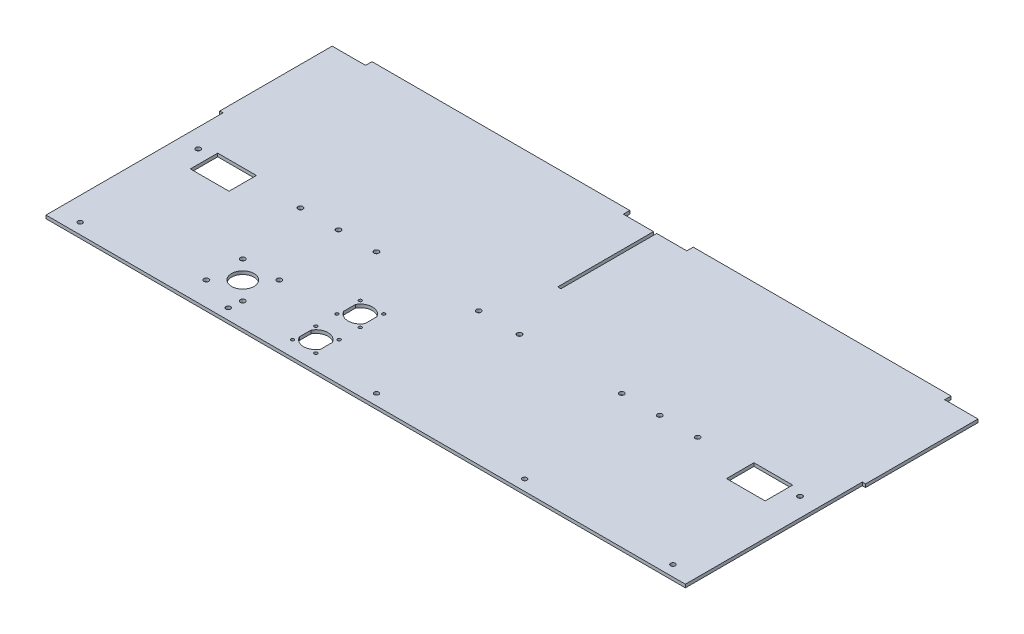
SolidWorks part; units mm, degrees
material "6061-T6 (SS)"
ref_plane "X-Y Datum" through (0, 0, 0) normal (0, 0, 1) x (1, 0, 0)
ref_plane "X-Z Datum" through (0, 0, 0) normal (0, 1, 0) x (1, 0, 0)
ref_plane "Y-Z Datum" through (0, 0, 0) normal (1, 0, 0) x (0, 0, -1)
sketch "Sketch1" plane through (0, 0, 0) normal (0, 1, 0) x (1, 0, 0)
  line L1 (0, 0) -> (629.9098, 0)
  line L2 (0, 0) -> (0, 147.6985)
  line L3 (0, 147.6985) -> (629.9098, 147.6985)
  line L4 (629.9098, 0) -> (629.9098, 147.6985)
extrude "Boss-Extrude1" add sketch "Sketch1" along normal blind 3.175
sketch "Sketch3" plane through (0, 0, -147.6985) normal (0, 0, -1) x (-1, 0, 0)
  line L0 (-629.9098, 0) -> (0, 0) construction
  line L1 (-629.9098, 0) -> (-629.9098, 3.175) construction
  line L2 (-629.9098, 3.175) -> (0, 3.175) construction
  line L3 (0, 0) -> (0, 3.175) construction
  line L4 (-600.2261, 0) -> (-346.2261, 0)
  line L5 (-600.2261, 0) -> (-600.2261, 3.175)
  line L6 (-600.2261, 3.175) -> (-346.2261, 3.175)
  line L7 (-346.2261, 0) -> (-346.2261, 3.175)
  line L8 (-283.6837, 0) -> (-29.6837, 0)
  line L9 (-283.6837, 0) -> (-283.6837, 3.175)
  line L10 (-283.6837, 3.175) -> (-29.6837, 3.175)
  line L11 (-29.6837, 0) -> (-29.6837, 3.175)
extrude "Boss-Extrude2" add sketch "Sketch3" along normal blind 6.35
sketch "Sketch4" plane through (0, 3.175, 0) normal (0, 1, 0) x (1, 0, 0)
  line L0 (346.2261, 147.6985) -> (283.6837, 147.6985) construction
  line L1 (313.3674, 53.332) -> (316.5424, 53.332)
  line L2 (313.3674, 53.332) -> (313.3674, 242.0649)
  line L3 (313.3674, 242.0649) -> (316.5424, 242.0649)
  line L4 (316.5424, 53.332) -> (316.5424, 242.0649)
  line L5 (313.3674, 53.332) -> (316.5424, 242.0649) construction
  line L6 (313.3674, 242.0649) -> (316.5424, 53.332) construction
  point P0 (314.9549, 147.6985)
extrude "Cut-Extrude1" cut sketch "Sketch4" against normal blind 3.175
sketch "Sketch6" plane through (0, 3.175, 0) normal (0, 1, 0) x (1, 0, 0)
  line L0 (314.9549, 53.332) -> (314.9549, 202.815) construction
  line L6 (629.9098, 36.9246) -> (633.0848, 36.9246)
  line L7 (633.0848, 147.6985) -> (633.0848, 36.9246)
  line L8 (629.9098, 147.6985) -> (633.0848, 147.6985)
  line L9 (629.9098, 147.6985) -> (629.9098, 36.9246)
  line L10 (0, 147.6985) -> (0, 36.9246)
  line L11 (0, 147.6985) -> (-3.175, 147.6985)
  line L12 (-3.175, 147.6985) -> (-3.175, 36.9246)
  line L13 (0, 36.9246) -> (-3.175, 36.9246)
extrude "Boss-Extrude4" add sketch "Sketch6" against normal blind 3.175
sketch "Sketch8" plane through (0, 3.175, 0) normal (0, 1, 0) x (1, 0, 0)
  line L1 (0, 0) -> (629.9098, 0)
  line L2 (0, 0) -> (0, -18.0442)
  line L3 (0, -18.0442) -> (629.9098, -18.0442)
  line L4 (629.9098, 0) -> (629.9098, -18.0442)
extrude "Boss-Extrude5" add sketch "Sketch8" against normal through all
sketch "Sketch9" plane through (0, 3.175, 0) normal (0, 1, 0) x (1, 0, 0)
  line L0 (0, -18.0442) -> (47.8104, -18.0442) construction
  line L1 (0, -18.0442) -> (629.9098, -18.0442) construction
  line L2 (314.9549, -18.0442) -> (314.9549, 180.2876) construction
  line L3 (30.0304, -36.0782) -> (65.5904, -36.0782)
  line L4 (30.0304, -36.0782) -> (30.0304, -0.0102)
  line L5 (30.0304, -0.0102) -> (65.5904, -0.0102)
  line L6 (65.5904, -36.0782) -> (65.5904, -0.0102)
  line L7 (30.0304, -36.0782) -> (65.5904, -0.0102) construction
  line L8 (30.0304, -0.0102) -> (65.5904, -36.0782) construction
  line L9 (599.8794, -0.0102) -> (564.3194, -0.0102)
  line L10 (564.3194, -36.0782) -> (564.3194, -0.0102)
  line L11 (599.8794, -36.0782) -> (564.3194, -36.0782)
  line L12 (599.8794, -36.0782) -> (599.8794, -0.0102)
extrude "Cut-Extrude2" [suppressed] cut sketch "Sketch9" against normal through all
sketch "Sketch10" plane through (0, 3.175, 0) normal (0, 1, 0) x (1, 0, 0)
  line L0 (313.3674, 53.332) -> (313.3674, -18.0442) construction
  line L1 (314.9549, -18.0442) -> (314.9549, -25.2417) construction
  line L2 (0, -18.0442) -> (629.9098, -18.0442) construction
  line L3 (313.3674, -18.0442) -> (281.6174, -18.0442) construction
  line L4 (348.2924, 0) -> (386.3924, 0) construction
  line L5 (281.6174, -18.0442) -> (243.5174, -18.0442) construction
  line L6 (281.6174, -18.0442) -> (281.6174, 0) construction
  line L7 (281.6174, 0) -> (243.5174, 0) construction
  line L8 (243.5174, -18.0442) -> (243.5174, 0) construction
  line L9 (386.3924, -18.0442) -> (386.3924, 0) construction
  line L10 (348.2924, -18.0442) -> (386.3924, -18.0442) construction
  line L11 (348.2924, -18.0442) -> (348.2924, 0) construction
  line L12 (0, -18.0442) -> (50.8, -18.0442) construction
  line L13 (0, -18.0442) -> (629.9098, -18.0442) construction
  line L22 (598.1598, 0) -> (560.0598, 0)
  line L23 (31.75, -36.0883) -> (69.85, -36.0883)
  line L24 (31.75, -36.0883) -> (31.75, 0)
  line L25 (31.75, 0) -> (69.85, 0)
  line L26 (69.85, -36.0883) -> (69.85, 0)
  line L27 (31.75, -36.0883) -> (69.85, 0) construction
  line L28 (31.75, 0) -> (69.85, -36.0883) construction
  line L29 (560.0598, -36.0883) -> (560.0598, 0)
  line L30 (598.1598, -36.0883) -> (560.0598, -36.0883)
  line L31 (598.1598, -36.0883) -> (598.1598, 0)
  line L32 (0, 36.9246) -> (0, -18.0442) construction
  dimension "D1" = 31.75
  dimension "D2" = 38.1
  dimension "D3" = 50.8
extrude "Cut-Extrude3" cut sketch "Sketch10" against normal through all
sketch "Sketch11" plane through (0, 3.175, 0) normal (0, 1, 0) x (1, 0, 0)
  line L2 (0, -18.0442) -> (0, -137.4242)
  line L3 (0, -137.4242) -> (629.9098, -137.4242)
  line L4 (629.9098, -18.0442) -> (629.9098, -137.4242)
  line L5 (314.9549, -18.0442) -> (629.9098, -137.4242) construction
  line L6 (0, -137.4242) -> (314.9549, -18.0442) construction
  line L7 (0, -18.0442) -> (31.75, -18.0442)
  line L8 (281.6174, -18.0442) -> (348.2924, -18.0442)
  line L10 (243.5174, -18.0442) -> (243.5174, -26.9519) construction
  line L11 (243.5174, -26.9519) -> (281.6174, -26.9519) construction
  line L12 (281.6174, -18.0442) -> (281.6174, -26.9519) construction
  line L14 (348.2924, -18.0442) -> (348.2924, -27.0662) construction
  line L15 (348.2924, -27.0662) -> (386.3924, -27.0662) construction
  line L16 (386.3924, -18.0442) -> (386.3924, -27.0662) construction
  line L17 (386.3924, -18.0442) -> (560.0598, -18.0442)
  line L18 (31.75, -18.0442) -> (31.75, -26.9519)
  line L19 (31.75, -26.9519) -> (69.85, -26.9519)
  line L20 (69.85, -26.9519) -> (69.85, -18.0442)
  line L21 (560.0598, -18.0442) -> (560.0598, -27.0662)
  line L22 (560.0598, -27.0662) -> (598.1598, -27.0662)
  line L23 (598.1598, -27.0662) -> (598.1598, -18.0442)
  line L24 (69.85, -18.0442) -> (243.5174, -18.0442)
  line L25 (598.1598, -18.0442) -> (629.9098, -18.0442)
  line L26 (243.5174, -18.0442) -> (281.6174, -18.0442)
  line L27 (348.2924, -18.0442) -> (386.3924, -18.0442)
  point P0 (314.9549, -18.0442)
extrude "Boss-Extrude6" add sketch "Sketch11" against normal through all
sketch "Sketch12" [suppressed] plane through (0, 3.175, 0) normal (0, 1, 0) x (1, 0, 0)
  line L1 (31.75, 0) -> (69.85, 0)
  line L2 (31.75, 0) -> (31.75, -18.0442)
  line L3 (31.75, -18.0442) -> (69.85, -18.0442)
  line L4 (69.85, 0) -> (69.85, -18.0442)
  line L5 (560.0598, 0) -> (598.1598, 0)
  line L6 (560.0598, 0) -> (560.0598, -18.0442)
  line L7 (560.0598, -18.0442) -> (598.1598, -18.0442)
  line L8 (598.1598, 0) -> (598.1598, -18.0442)
extrude "Boss-Extrude7" [suppressed] add sketch "Sketch12" against normal through all
sketch "Sketch13" plane through (0, 0, 0) normal (0, -1, 0) x (1, 0, 0)
  line L0 (229.2316, 116.5107) -> (229.2316, 105.1529) construction
  line L1 (249.2316, 116.5107) -> (249.2316, 105.1529) construction
  line L2 (249.2316, 72.6906) -> (249.2316, 61.3328) construction
  line L3 (229.2316, 72.6906) -> (229.2316, 61.3328) construction
  line L4 (249.7396, 116.6433) -> (249.7396, 105.0203)
  line L5 (228.7236, 116.6433) -> (228.7236, 105.0203)
  line L6 (249.7396, 72.8232) -> (249.7396, 61.2001)
  line L7 (228.7236, 72.8232) -> (228.7236, 61.2001)
  line L8 (2.2083, 136.32) -> (632.1181, 136.32) construction
  line L9 (2.2083, 136.32) -> (2.2083, 49.1456) construction
  line L10 (2.2083, 49.1456) -> (632.1181, 49.1456) construction
  line L11 (632.1181, 136.32) -> (632.1181, 49.1456) construction
  circle A0 centre (227.7316, 99.3318) radius 1.55
  circle A1 centre (227.7316, 122.3318) radius 1.55
  circle A2 centre (250.7316, 99.3318) radius 1.55
  circle A3 centre (250.7316, 122.3318) radius 1.55
  circle A4 centre (152.3285, 95.8779) radius 11.049
  circle A5 centre (227.7316, 78.5117) radius 1.55
  circle A6 centre (227.7316, 55.5117) radius 1.55
  circle A7 centre (250.7316, 55.5117) radius 1.55
  circle A8 centre (250.7316, 78.5117) radius 1.55
  arc A9 (249.2316, 72.6906) -> (229.2316, 72.6906) centre (239.2316, 67.0117) ccw construction
  arc A10 (249.2316, 61.3328) -> (229.2316, 61.3328) centre (239.2316, 67.0117) cw construction
  arc A11 (229.2316, 116.5107) -> (249.2316, 116.5107) centre (239.2316, 110.8318) cw construction
  arc A12 (229.2316, 105.1529) -> (249.2316, 105.1529) centre (239.2316, 110.8318) ccw construction
  arc A13 (228.7236, 105.0203) -> (249.7396, 105.0203) centre (239.2316, 110.8318) ccw
  arc A14 (228.7236, 116.6433) -> (249.7396, 116.6433) centre (239.2316, 110.8318) cw
  arc A15 (249.7396, 61.2001) -> (228.7236, 61.2001) centre (239.2316, 67.0117) cw
  arc A16 (249.7396, 72.8232) -> (228.7236, 72.8232) centre (239.2316, 67.0117) ccw
extrude "Cut-Extrude4" cut sketch "Sketch13" against normal through all
sketch "Sketch14" plane through (0, 0, 0) normal (0, -1, 0) x (1, 0, 0)
  line L0 (0, 137.4242) -> (653.3937, 137.4242) construction
  line L1 (0, 137.4242) -> (0, -17.9044) construction
  line L2 (0, -17.9044) -> (653.3937, -17.9044) construction
  line L3 (653.3937, 137.4242) -> (653.3937, -17.9044) construction
  point P0 (11.811, 127.2642)
  point P1 (163.383, 127.2642)
  point P2 (314.9549, 127.2642)
  point P3 (466.5269, 127.2642)
  point P4 (618.0988, 127.2642)
  point P5 (618.0988, 38.1102)
  point P6 (466.5269, 38.1102)
  point P7 (314.9549, 38.1102)
  point P8 (163.383, 38.1102)
  point P9 (11.811, 38.1102)
sketch "Sketch17" [suppressed] plane through (0, 3.175, 0) normal (0, 1, 0) x (1, 0, 0)
  line L1 (243.5174, -18.0442) -> (281.6174, -18.0442)
  line L2 (243.5174, -18.0442) -> (243.5174, 0)
  line L3 (243.5174, 0) -> (281.6174, 0)
  line L4 (281.6174, -18.0442) -> (281.6174, 0)
  line L5 (348.2924, -18.0442) -> (386.3924, -18.0442)
  line L6 (348.2924, -18.0442) -> (348.2924, 0)
  line L7 (348.2924, 0) -> (386.3924, 0)
  line L8 (386.3924, -18.0442) -> (386.3924, 0)
extrude "Cut-Extrude5" [suppressed] cut sketch "Sketch17" against normal through all
sketch "Sketch18" [suppressed] plane through (0, 3.175, 0) normal (0, 1, 0) x (1, 0, 0)
  line L0 (0, 36.9246) -> (0, -18.0442) construction
  line L1 (104.9274, 0.4059) -> (143.0274, 0.4059)
  line L2 (104.9274, 0.4059) -> (104.9274, -18.0442)
  line L3 (104.9274, -18.0442) -> (143.0274, -18.0442)
  line L4 (143.0274, 0.4059) -> (143.0274, -18.0442)
  line L10 (314.752, 53.332) -> (314.752, 40.2478) construction
  line L16 (386.3924, -18.0442) -> (629.9098, -18.0442) construction
  line L17 (567.7073, -18.0442) -> (529.6073, -18.0442)
  line L18 (567.7073, -18.0442) -> (567.7073, 0.4059)
  line L19 (567.7073, 0.4059) -> (529.6073, 0.4059)
  line L20 (529.6073, -18.0442) -> (529.6073, 0.4059)
  line L21 (0, -18.0442) -> (243.5174, -18.0442) construction
  line L22 (629.9098, -18.0442) -> (629.9098, 36.9246) construction
  dimension "D1" = 38.1
  dimension "D2" = 104.9274
  dimension "D3" = 38.1
  dimension "D4" = 62.2025
extrude "Cut-Extrude6" [suppressed] cut sketch "Sketch18" against normal through all
sketch "Sketch20" plane through (0, 0, 0) normal (0, -1, 0) x (1, 0, 0)
  line L0 (269.9465, 71.4811) -> (278.9364, 71.4811)
  line L1 (258.3414, 113.1615) -> (278.9364, 113.1615)
  line L2 (258.3414, 113.1615) -> (258.3414, 110.2194)
  line L3 (258.3414, 110.2194) -> (278.9364, 110.2194)
  line L4 (278.9364, 113.1615) -> (278.9364, 110.2194)
  line L5 (258.3414, 71.4811) -> (266.1871, 71.4811)
  line L6 (258.3414, 71.4811) -> (258.3414, 69.3563)
  line L7 (258.3414, 69.3563) -> (266.1871, 69.3563)
  line L8 (278.9364, 71.4811) -> (278.9364, 69.3563)
  line L9 (266.1871, 79) -> (269.9465, 79)
  line L10 (266.1871, 79) -> (266.1871, 71.4811)
  line L11 (266.1871, 61.8375) -> (269.9465, 61.8375)
  line L12 (269.9465, 79) -> (269.9465, 71.4811)
  line L13 (269.9465, 69.3563) -> (269.9465, 61.8375)
  line L14 (269.9465, 69.3563) -> (278.9364, 69.3563)
  line L15 (266.1871, 69.3563) -> (266.1871, 61.8375)
extrude "Cut-Extrude7" cut sketch "Sketch20" against normal blind 1.27
sketch "Sketch21" plane through (0, 3.175, 0) normal (0, 1, 0) x (1, 0, 0)
  line L0 (0, -137.4242) -> (8.6479, -137.4242) construction
  line L1 (0, -137.4242) -> (0, -125.2168) construction
  line L2 (0, -125.2168) -> (8.6479, -125.2168) construction
  line L3 (8.6479, -137.4242) -> (8.6479, -125.2168) construction
  line L4 (314.9549, 53.332) -> (314.9549, 36.3364) construction
  line L5 (313.3674, 53.332) -> (316.5424, 53.332) construction
  circle A1 centre (168.9435, -126.7866) radius 2.25
  circle A2 centre (314.9549, -126.7866) radius 2.25
  circle A3 centre (460.9663, -126.7866) radius 2.25
  circle A4 centre (606.9777, -126.7866) radius 2.25
  circle A5 centre (22.9321, -126.7866) radius 2.25
  point P1 (168.9435, -126.7866)
  point P2 (314.9549, -126.7866)
  point P3 (460.9663, -126.7866)
  point P4 (606.9777, -126.7866)
  point P9 (0, -137.4242)
extrude "Cut-Extrude8" cut sketch "Sketch21" against normal through all
sketch "Sketch22" [suppressed] plane through (0, 3.175, 0) normal (0, 1, 0) x (1, 0, 0)
  line L6 (0, -7.747) -> (104.9274, -7.747) construction
  line L9 (0, 36.9246) -> (0, -18.0442) construction
  line L12 (104.9274, 0.4059) -> (104.9274, -18.0442) construction
  line L15 (143.0274, -7.747) -> (243.5174, -7.747) construction
  line L16 (143.0274, -18.0442) -> (143.0274, 0.4059) construction
  line L17 (243.5174, 0) -> (243.5174, -18.0442) construction
  line L18 (281.6174, -7.747) -> (348.2924, -7.747) construction
  line L19 (281.6174, -18.0442) -> (281.6174, 0) construction
  line L20 (348.2924, 0) -> (348.2924, -18.0442) construction
  line L21 (386.3924, -7.747) -> (529.6073, -7.747) construction
  line L24 (386.3924, -18.0442) -> (386.3924, 0) construction
  line L25 (529.6073, 0.4059) -> (529.6073, -18.0442) construction
  line L26 (567.7073, -7.747) -> (629.9098, -7.747) construction
  line L27 (567.7073, -18.0442) -> (567.7073, 0.4059) construction
  line L28 (629.9098, -18.0442) -> (629.9098, 36.9246) construction
  circle A0 centre (53.9598, -7.747) radius 1
  circle A1 centre (193.2724, -7.747) radius 1
  circle A2 centre (314.9549, -7.747) radius 1
  circle A3 centre (457.9999, -7.747) radius 1
  circle A4 centre (597.3125, -7.747) radius 1
extrude "Cut-Extrude9" [suppressed] cut sketch "Sketch22" against normal through all
sketch "Sketch23" plane through (0, 3.175, 0) normal (0, 1, 0) x (1, 0, 0)
  line L0 (538.3475, -12.829) -> (538.3475, -6.729) construction
  line L1 (375.4057, -12.829) -> (375.4057, -6.729) construction
  line L2 (254.5042, -12.829) -> (254.5042, -6.729) construction
  line L3 (91.5623, -12.829) -> (91.5623, -6.729) construction
  line L4 (629.9098, -137.4242) -> (403.1779, -137.4242) construction
  line L5 (629.9098, -137.4242) -> (629.9098, -43.8281) construction
  line L6 (629.9098, -43.8281) -> (403.1779, -43.8281) construction
  line L7 (403.1779, -137.4242) -> (403.1779, -43.8281) construction
  circle A0 centre (538.3475, -9.779) radius 2.25
  circle A1 centre (375.4057, -9.779) radius 2.25
  circle A2 centre (254.5042, -9.779) radius 2.25
  circle A3 centre (91.5623, -9.779) radius 2.25
  point P20 (629.9098, -137.4242)
extrude "Cut-Extrude10" [suppressed] cut sketch "Sketch23" against normal through all
sketch "Sketch24" [suppressed] plane through (0, 3.175, 0) normal (0, 1, 0) x (1, 0, 0)
  line L0 (314.9549, -18.0442) -> (314.9549, -44.4855) construction
  line L1 (0, -18.0442) -> (5.08, -18.0442)
  line L2 (0, -18.0442) -> (0, -5.3442)
  line L3 (0, -5.3442) -> (5.08, -5.3442)
  line L4 (5.08, -18.0442) -> (5.08, -5.3442)
  line L6 (629.9098, -5.3442) -> (624.8298, -5.3442)
  line L7 (624.8298, -18.0442) -> (624.8298, -5.3442)
  line L8 (629.9098, -18.0442) -> (624.8298, -18.0442)
  line L9 (629.9098, -18.0442) -> (629.9098, -5.3442)
extrude "Cut-Extrude11" [suppressed] cut sketch "Sketch24" against normal through all
hole_wizard "M4 Clearance Hole1" [suppressed] positions "Sketch25" profile "Sketch26" hole size "M4" standard "ANSI Metric"
sketch "Sketch25" plane through (0, 3.175, 0) normal (0, 1, 0) x (1, 0, 0)
  point P0 (53.9598, -7.747)
  point P3 (193.2724, -7.747)
  point P6 (314.9549, -7.747)
  point P9 (457.9999, -7.747)
  point P12 (597.3125, -7.747)
sketch "Sketch26" plane through (53.9598, 3.175, 7.747) normal (1, 0, 0) x (0, 0, 1)
  line L0 (0, 0) -> (0, 3.175)
  line L1 (0, 3.175) -> (2.4, 3.175)
  line L2 (2.4, 3.175) -> (2.4, 0)
  line L5 (2.4, 0) -> (0, 0)
  line L11 (0, -6.35) -> (0, 107.95) construction
  dimension "Thru Hole Dia." = 4.8
  dimension "Thru Hole Depth" = 3.175
sketch "Sketch27" plane through (0, 3.175, 0) normal (0, 1, 0) x (1, 0, 0)
  circle A0 centre (134.368, -77.9173) radius 2.4
  circle A1 centre (170.289, -77.9173) radius 2.4
  circle A2 centre (170.289, -113.8384) radius 2.4
  circle A3 centre (134.368, -113.8384) radius 2.4
  point P4 (152.3285, -95.8779)
extrude "Cut-Extrude12" cut sketch "Sketch27" against normal through all
sketch "Sketch28" plane through (0, 3.175, 0) normal (0, 1, 0) x (1, 0, 0)
  line L0 (629.9098, -18.0442) -> (0, -18.0442) construction
  line L1 (629.9098, -18.0442) -> (629.9098, 147.6985) construction
  line L2 (629.9098, 147.6985) -> (0, 147.6985) construction
  line L3 (0, -18.0442) -> (0, 147.6985) construction
  line L4 (613.8026, -5.9968) -> (609.002, -5.9968)
  line L5 (513.0512, -5.9968) -> (508.2506, -5.9968)
  line L6 (475.6264, -5.9968) -> (470.8258, -5.9968)
  line L7 (438.2017, -5.9968) -> (433.4011, -5.9968)
  line L8 (337.45, -5.9968) -> (332.6497, -5.9968)
  line L9 (314.9549, 53.332) -> (314.9549, 20.4386) construction
  line L10 (292.4599, -5.9968) -> (297.2602, -5.9968)
  line L11 (191.7082, -5.9968) -> (196.5088, -5.9968)
  line L12 (154.2834, -5.9968) -> (159.084, -5.9968)
  line L13 (116.8586, -5.9968) -> (121.6592, -5.9968)
  line L14 (16.1072, -5.9968) -> (20.9078, -5.9968)
hole_wizard "M4 Clearance Hole2" positions "Sketch29" profile "Sketch30" hole size "M4" standard "ANSI Metric" end condition through all
sketch "Sketch29" plane through (0, 3.175, 0) normal (0, 1, 0) x (1, 0, 0)
  line L0 (16.1072, -5.9968) -> (20.9078, -5.9968) construction
  line L1 (116.8586, -5.9968) -> (121.6592, -5.9968) construction
  line L2 (154.2834, -5.9968) -> (159.084, -5.9968) construction
  line L3 (191.7082, -5.9968) -> (196.5088, -5.9968) construction
  line L4 (292.4599, -5.9968) -> (297.2602, -5.9968) construction
  line L5 (337.45, -5.9968) -> (332.6497, -5.9968) construction
  line L6 (438.2017, -5.9968) -> (433.4011, -5.9968) construction
  line L7 (475.6264, -5.9968) -> (470.8258, -5.9968) construction
  line L8 (513.0512, -5.9968) -> (508.2506, -5.9968) construction
  line L9 (613.8026, -5.9968) -> (609.002, -5.9968) construction
  point P0 (18.5075, -5.9968)
  point P4 (119.2589, -5.9968)
  point P8 (156.6837, -5.9968)
  point P12 (194.1085, -5.9968)
  point P16 (294.86, -5.9968)
  point P20 (335.0498, -5.9968)
  point P24 (435.8014, -5.9968)
  point P28 (473.2261, -5.9968)
  point P32 (510.6509, -5.9968)
  point P36 (611.4023, -5.9968)
sketch "Sketch30" plane through (18.5075, 3.175, 5.9968) normal (1, 0, 0) x (0, 0, 1)
  line L0 (0, 0) -> (0, 3.175)
  line L1 (0, 3.175) -> (2.4, 3.175)
  line L2 (2.4, 3.175) -> (2.4, 0)
  line L5 (2.4, 0) -> (0, 0)
  line L11 (0, -6.35) -> (0, 107.95) construction
  dimension "Thru Hole Dia." = 4.8
  dimension "Thru Hole Depth" = 3.175
